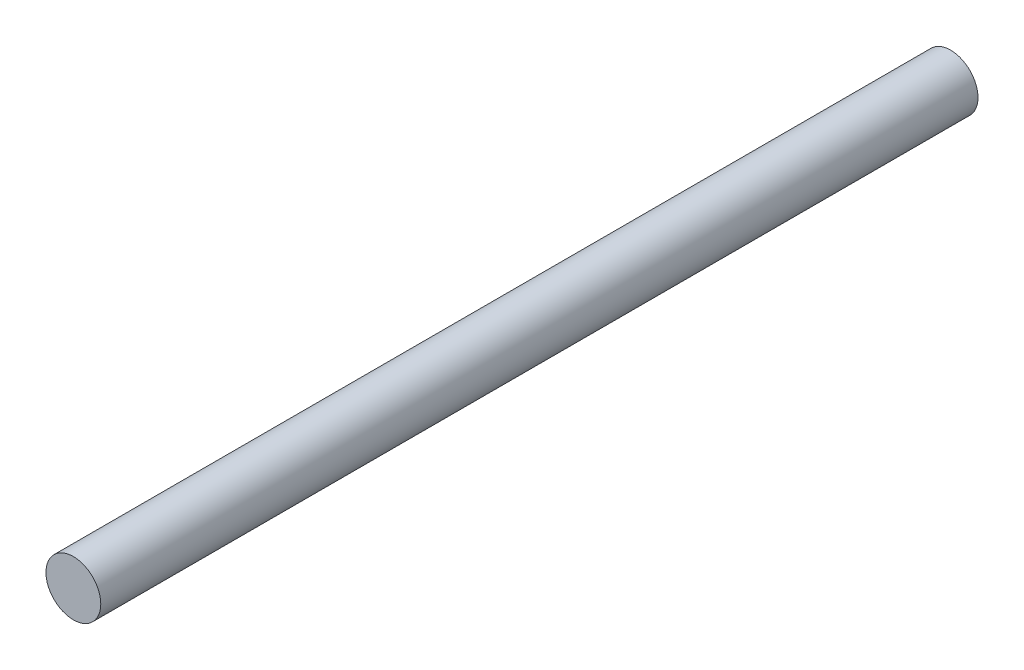
SolidWorks part; units mm, degrees
ref_plane "Front" through (0, 0, 0) normal (0, 0, 1) x (1, 0, 0)
ref_plane "Top" through (0, 0, 0) normal (0, 1, 0) x (1, 0, 0)
ref_plane "Right" through (0, 0, 0) normal (1, 0, 0) x (0, 0, -1)
sketch "Sketch1" plane through (0, 0, 0) normal (0, 0, 1) x (1, 0, 0)
  circle A0 centre (0, 0) radius 0.75
  dimension "D1" = 1.5
extrude "Boss-Extrude1" add sketch "Sketch1" along normal blind 24
